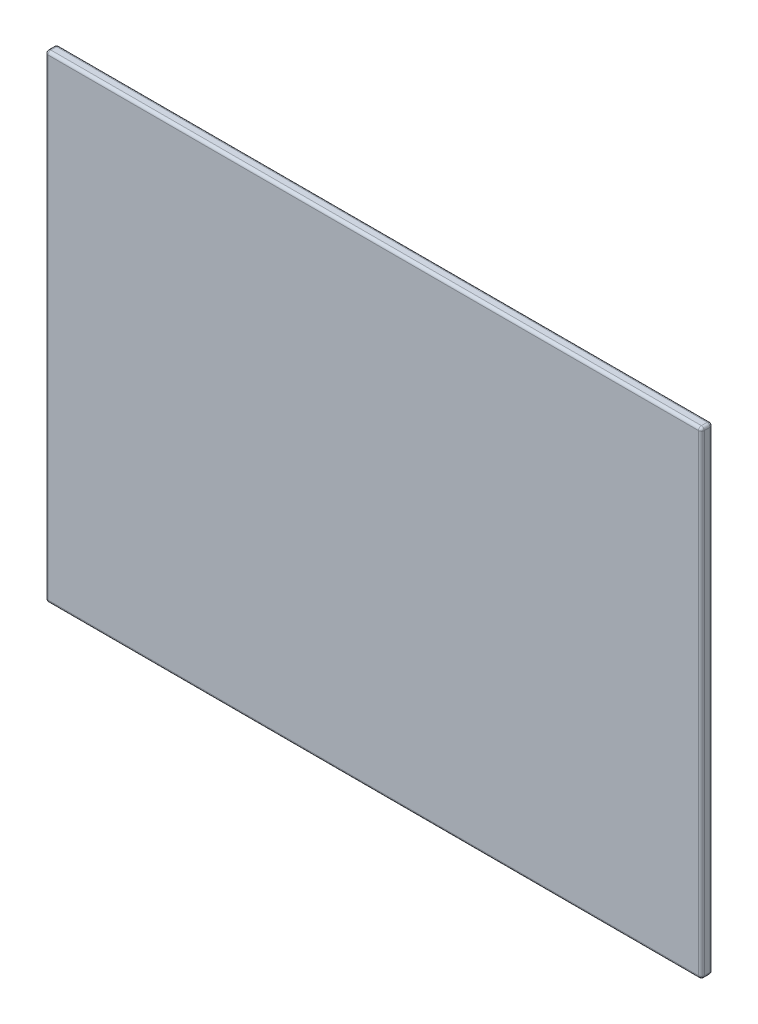
SolidWorks part; units mm, degrees
ref_plane "Front Plane" through (0, 0, 0) normal (0, 0, 1) x (1, 0, 0)
ref_plane "Top Plane" through (0, 0, 0) normal (0, 1, 0) x (1, 0, 0)
ref_plane "Right Plane" through (0, 0, 0) normal (1, 0, 0) x (0, 0, -1)
sketch "Sketch1" plane through (0, 0, 0) normal (0, 0, 1) x (1, 0, 0)
  line L1 (-57.35, -41.75) -> (57.35, -41.75)
  line L2 (-57.35, -41.75) -> (-57.35, 41.75)
  line L3 (-57.35, 41.75) -> (57.35, 41.75)
  line L4 (57.35, -41.75) -> (57.35, 41.75)
  line L5 (-57.35, -41.75) -> (57.35, 41.75) construction
  line L6 (-57.35, 41.75) -> (57.35, -41.75) construction
  point P0 (0, 0)
  dimension "D1" = 114.7
  dimension "D2" = 83.5
extrude "Boss-Extrude1" add sketch "Sketch1" along normal blind 2
fillet "Fillet1" radius 0.5 12 edges at (0, -41.75, 2) (0, -41.75, 0) (-57.35, 0, 2) (-57.35, -41.75, 1) (-57.35, 0, 0) (0, 41.75, 2) (-57.35, 41.75, 1) (0, 41.75, 0) (57.35, -41.75, 1) (57.35, 0, 2) (57.35, 41.75, 1) (57.35, 0, 0)
